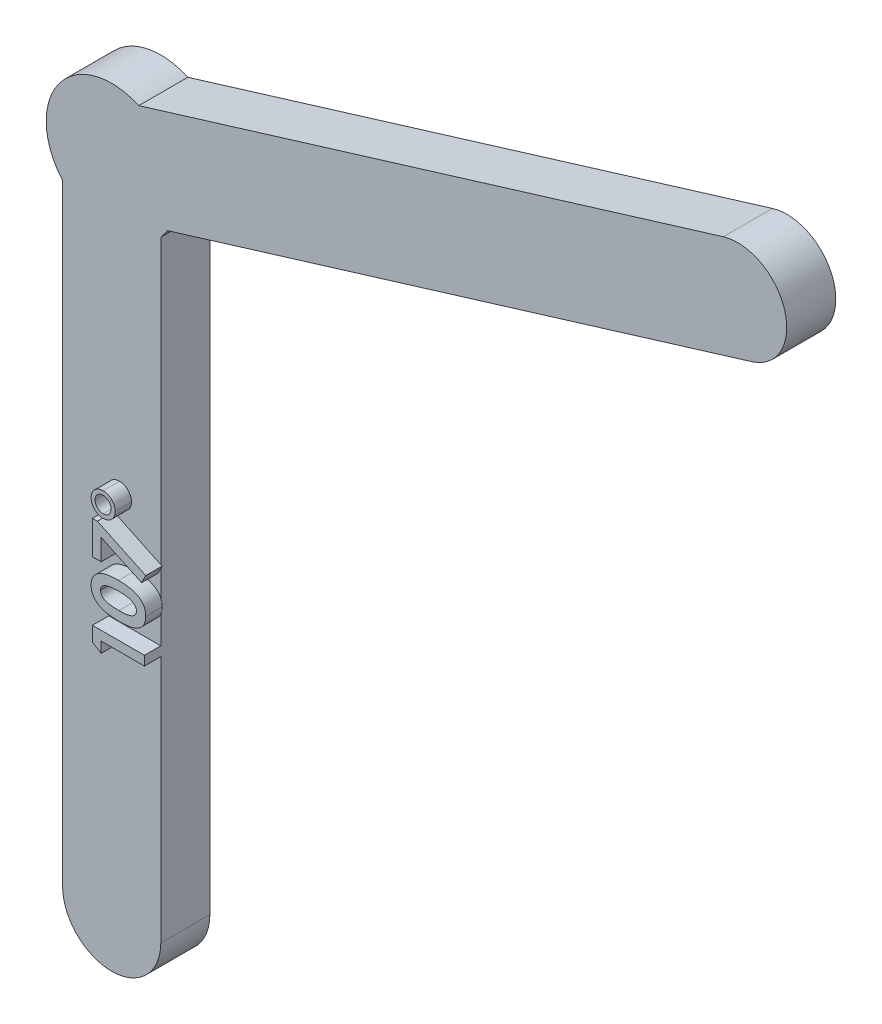
SolidWorks part; units mm, degrees
ref_plane "Front Plane" through (0, 0, 0) normal (0, 0, 1) x (1, 0, 0)
ref_plane "Top Plane" through (0, 0, 0) normal (0, 1, 0) x (1, 0, 0)
ref_plane "Right Plane" through (0, 0, 0) normal (1, 0, 0) x (0, 0, -1)
sketch "Sketch2" plane through (0, 0, 0) normal (0, 0, 1) x (1, 0, 0)
  line L0 (0, 0) -> (0, -40) construction
  line L1 (0, 0) -> (38.2522, 11.6949) construction
  line L2 (37.3751, 14.5638) -> (39.1293, 8.826) construction
  line L3 (-3, -40) -> (3, -40) construction
  line L4 (-3, -40) -> (-3, -2.6458)
  line L5 (3, -40) -> (3, -2.6458)
  line L6 (37.3751, 14.5638) -> (1.653, 3.6425)
  line L7 (39.1293, 8.826) -> (3.4073, -2.0954)
  arc A0 (1.653, 3.6425) -> (-3, -2.6458) centre (0, 0) ccw
  arc A1 (-3, -40) -> (3, -40) centre (0, -40) ccw
  arc A2 (37.3751, 14.5638) -> (39.1293, 8.826) centre (38.2522, 11.6949) cw
  arc A3 (3, -2.6458) -> (3.4073, -2.0954) centre (0, 0) ccw
  point P12 (38.2522, 11.6949)
  dimension "D3" = 3
  dimension "D4" = 8
  dimension "D1" = 40
  dimension "D2" = 107
extrude "Boss-Extrude1" add sketch "Sketch2" along normal blind 3
sketch "Sketch3" plane through (0, 0, 3) normal (0, 0, 1) x (1, 0, 0)
  text T0 "<b>107°</b>"
extrude "Boss-Extrude2" add sketch "Sketch3" along normal blind 1
